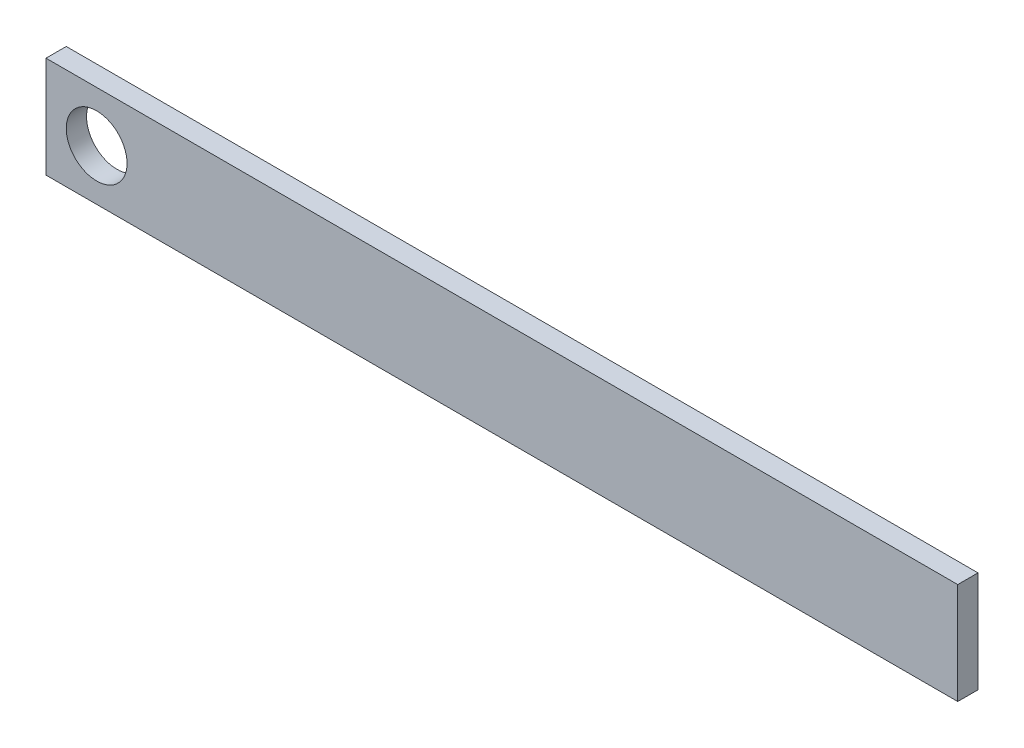
SolidWorks part; units mm, degrees
ref_plane "前视基准面" through (0, 0, 0) normal (0, 0, 1) x (1, 0, 0)
ref_plane "上视基准面" through (0, 0, 0) normal (0, 1, 0) x (1, 0, 0)
ref_plane "右视基准面" through (0, 0, 0) normal (1, 0, 0) x (0, 0, -1)
sketch "草图1" plane through (0, 0, 0) normal (0, 0, 1) x (1, 0, 0)
  line L0 (-10.063, 5) -> (-10.063, 0) construction
  line L1 (32.437, 5) -> (-12.563, 5)
  line L2 (32.437, 5) -> (32.437, 0)
  line L4 (-12.563, 5) -> (-12.563, 0)
  line L5 (32.437, 0) -> (-12.563, 0)
  circle A0 centre (-10.063, 2.5) radius 1.5
  point P0 (0, 0)
  dimension "D1" = 45
  dimension "D3" = 2.5
  dimension "D4" = 2.5
extrude "凸台-拉伸1" add sketch "草图1" along normal blind 1
